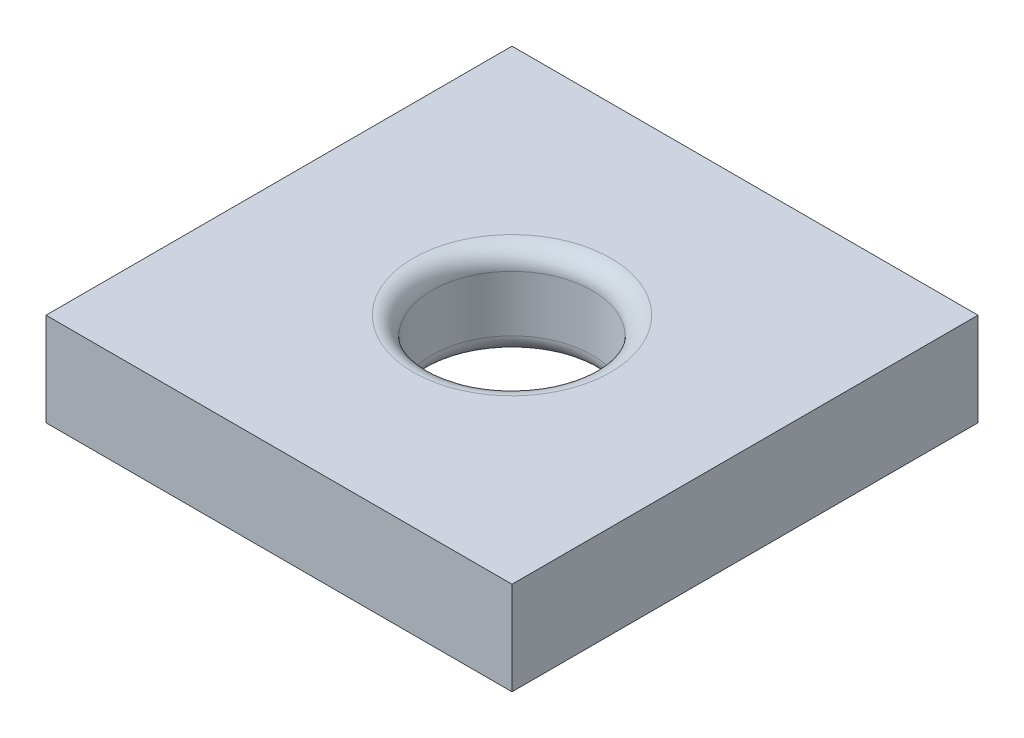
SolidWorks part; units mm, degrees
ref_plane "Plan de face" through (0, 0, 0) normal (0, 0, 1) x (1, 0, 0)
ref_plane "Plan de dessus" through (0, 0, 0) normal (0, 1, 0) x (1, 0, 0)
ref_plane "Plan de droite" through (0, 0, 0) normal (1, 0, 0) x (0, 0, -1)
sketch "Esquisse1" plane through (0, 0, 0) normal (0, 1, 0) x (1, 0, 0)
  line L1 (-25, 25) -> (0, 25)
  line L2 (-25, 25) -> (-25, 0)
  line L3 (-25, 0) -> (0, 0)
  line L4 (0, 25) -> (0, 0)
  point P4 (0, 0)
  dimension "D1" = 25
extrude "Boss.-Extru.1" add sketch "Esquisse1" along normal blind 5
sketch "Esquisse2" plane through (0, 5, 0) normal (0, 1, 0) x (1, 0, 0)
  line L0 (-25, 0) -> (0, 0) construction
  line L1 (0, 0) -> (0, 25) construction
  circle A0 centre (-12.5, 12.5) radius 4.3
  dimension "D1" = 8.6
  dimension "D2" = 12.5
  dimension "D3" = 12.5
extrude "Enlèv. mat.-Extru.1" cut sketch "Esquisse2" against normal up to next
fillet "Congé2" radius 1 1 edges at (-12.5, 0, -8.2)
fillet "Congé3" radius 1 1 edges at (-12.5, 5, -8.2)
equation "\"D2@Esquisse2\"=\"D1@Esquisse1\"/2"
equation "\"D3@Esquisse2\"=\"D1@Esquisse1\"/2"
